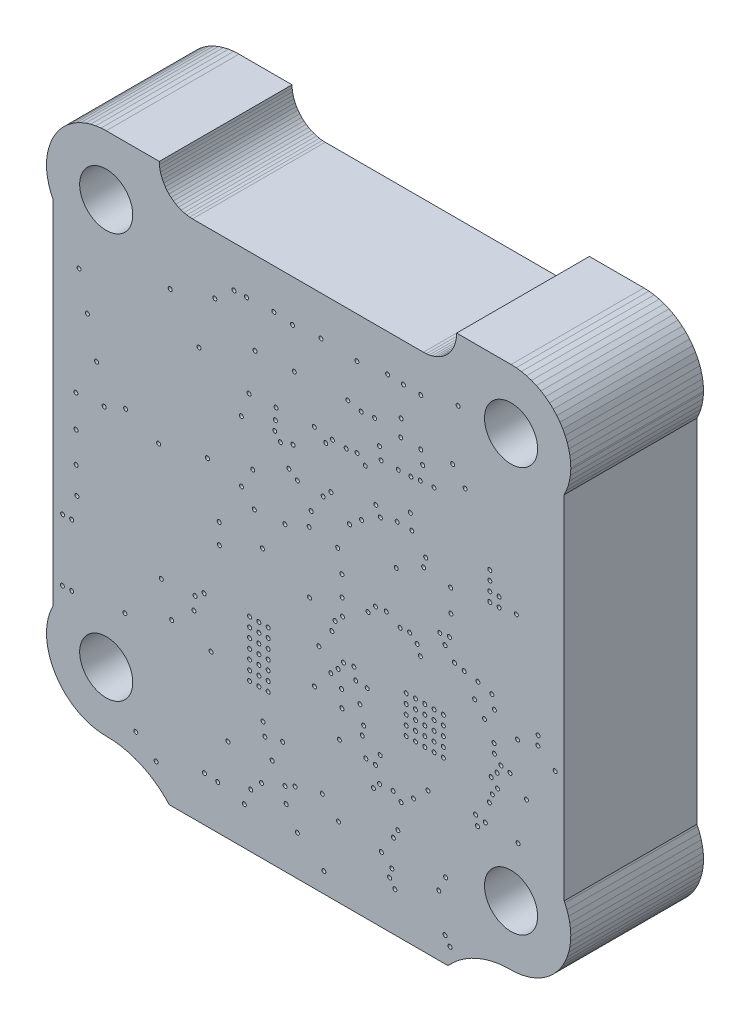
SolidWorks part; units mm, degrees
ref_plane "Спереди" through (0, 0, 0) normal (0, 0, 1) x (1, 0, 0)
ref_plane "Сверху" through (0, 0, 0) normal (0, 1, 0) x (1, 0, 0)
ref_plane "Справа" through (0, 0, 0) normal (1, 0, 0) x (0, 0, -1)
sketch "Model" plane through (0, 0, 0) normal (0, 0, 1) x (1, 0, 0)
  line L0 (0, 6.6) -> (0.0171, 6.2078)
  line L1 (0.0171, 6.2078) -> (0.0684, 5.8186)
  line L2 (0.0684, 5.8186) -> (0.1533, 5.4353)
  line L3 (0.1533, 5.4353) -> (0.2714, 5.0609)
  line L4 (0.2714, 5.0609) -> (0.4216, 4.6982)
  line L5 (0.4216, 4.6982) -> (0.6029, 4.35)
  line L6 (0.6029, 4.35) -> (0.8138, 4.0189)
  line L7 (0.8138, 4.0189) -> (1.0528, 3.7075)
  line L8 (1.0528, 3.7075) -> (1.318, 3.418)
  line L9 (1.318, 3.418) -> (1.6075, 3.1528)
  line L10 (1.6075, 3.1528) -> (1.9189, 2.9138)
  line L11 (1.9189, 2.9138) -> (2.25, 2.7029)
  line L12 (2.25, 2.7029) -> (2.5982, 2.5216)
  line L13 (2.5982, 2.5216) -> (2.9609, 2.3714)
  line L14 (2.9609, 2.3714) -> (3.3353, 2.2533)
  line L15 (3.3353, 2.2533) -> (3.7186, 2.1684)
  line L16 (3.7186, 2.1684) -> (4.1078, 2.1171)
  line L17 (4.1078, 2.1171) -> (4.5, 2.1)
  line L18 (4.5, 2.1) -> (5.0556, 2.0776)
  line L19 (5.0556, 2.0776) -> (5.6071, 2.0069)
  line L20 (5.6071, 2.0069) -> (6.1503, 1.8884)
  line L21 (6.1503, 1.8884) -> (6.6811, 1.723)
  line L22 (6.6811, 1.723) -> (7.1955, 1.5119)
  line L23 (7.1955, 1.5119) -> (7.6896, 1.2569)
  line L24 (7.6896, 1.2569) -> (8.1595, 0.9597)
  line L25 (8.1595, 0.9597) -> (8.6018, 0.6227)
  line L26 (8.6018, 0.6227) -> (9.013, 0.2484)
  line L27 (9.013, 0.2484) -> (9.25, 0)
  line L28 (9.25, 0) -> (30.25, 0)
  line L29 (30.25, 0) -> (30.6405, 0.3959)
  line L30 (30.6405, 0.3959) -> (31.0639, 0.7562)
  line L31 (31.0639, 0.7562) -> (31.5172, 1.0782)
  line L32 (31.5172, 1.0782) -> (31.9968, 1.3595)
  line L33 (31.9968, 1.3595) -> (32.4991, 1.598)
  line L34 (32.4991, 1.598) -> (33.0202, 1.7917)
  line L35 (33.0202, 1.7917) -> (33.5563, 1.9393)
  line L36 (33.5563, 1.9393) -> (34.1032, 2.0396)
  line L37 (34.1032, 2.0396) -> (34.6567, 2.0919)
  line L38 (34.6567, 2.0919) -> (35, 2.1)
  line L39 (35, 2.1) -> (35.3922, 2.1171)
  line L40 (35.3922, 2.1171) -> (35.7814, 2.1684)
  line L41 (35.7814, 2.1684) -> (36.1647, 2.2533)
  line L42 (36.1647, 2.2533) -> (36.5391, 2.3714)
  line L43 (36.5391, 2.3714) -> (36.9018, 2.5216)
  line L44 (36.9018, 2.5216) -> (37.25, 2.7029)
  line L45 (37.25, 2.7029) -> (37.5811, 2.9138)
  line L46 (37.5811, 2.9138) -> (37.8925, 3.1528)
  line L47 (37.8925, 3.1528) -> (38.182, 3.418)
  line L48 (38.182, 3.418) -> (38.4472, 3.7075)
  line L49 (38.4472, 3.7075) -> (38.6862, 4.0189)
  line L50 (38.6862, 4.0189) -> (38.8971, 4.35)
  line L51 (38.8971, 4.35) -> (39.0784, 4.6982)
  line L52 (39.0784, 4.6982) -> (39.2286, 5.0609)
  line L53 (39.2286, 5.0609) -> (39.3467, 5.4353)
  line L54 (39.3467, 5.4353) -> (39.4316, 5.8186)
  line L55 (39.4316, 5.8186) -> (39.4829, 6.2078)
  line L56 (39.4829, 6.2078) -> (39.5, 6.6)
  line L57 (39.5, 6.6) -> (39.4778, 6.9908)
  line L58 (39.4778, 6.9908) -> (39.4216, 7.3781)
  line L59 (39.4216, 7.3781) -> (39.3319, 7.7591)
  line L60 (39.3319, 7.7591) -> (39.2093, 8.1308)
  line L61 (39.2093, 8.1308) -> (39.0547, 8.4904)
  line L62 (39.0547, 8.4904) -> (39, 8.6)
  line L63 (39, 8.6) -> (39, 35.1)
  line L64 (39, 35.1) -> (39.1643, 35.4552)
  line L65 (39.1643, 35.4552) -> (39.297, 35.8235)
  line L66 (39.297, 35.8235) -> (39.3971, 36.2018)
  line L67 (39.3971, 36.2018) -> (39.4638, 36.5875)
  line L68 (39.4638, 36.5875) -> (39.4967, 36.9775)
  line L69 (39.4967, 36.9775) -> (39.5, 37.1)
  line L70 (39.5, 37.1) -> (39.4829, 37.4922)
  line L71 (39.4829, 37.4922) -> (39.4316, 37.8814)
  line L72 (39.4316, 37.8814) -> (39.3467, 38.2647)
  line L73 (39.3467, 38.2647) -> (39.2286, 38.6391)
  line L74 (39.2286, 38.6391) -> (39.0784, 39.0018)
  line L75 (39.0784, 39.0018) -> (38.8971, 39.35)
  line L76 (38.8971, 39.35) -> (38.6862, 39.6811)
  line L77 (38.6862, 39.6811) -> (38.4472, 39.9925)
  line L78 (38.4472, 39.9925) -> (38.182, 40.282)
  line L79 (38.182, 40.282) -> (37.8925, 40.5472)
  line L80 (37.8925, 40.5472) -> (37.5811, 40.7862)
  line L81 (37.5811, 40.7862) -> (37.25, 40.9971)
  line L82 (37.25, 40.9971) -> (36.9018, 41.1784)
  line L83 (36.9018, 41.1784) -> (36.5391, 41.3286)
  line L84 (36.5391, 41.3286) -> (36.1647, 41.4467)
  line L85 (36.1647, 41.4467) -> (35.7814, 41.5316)
  line L86 (35.7814, 41.5316) -> (35.3922, 41.5829)
  line L87 (35.3922, 41.5829) -> (35, 41.6)
  line L88 (35, 41.6) -> (30.9, 41.6)
  line L89 (30.9, 41.6) -> (30.8905, 41.3821)
  line L90 (30.8905, 41.3821) -> (30.862, 41.1659)
  line L91 (30.862, 41.1659) -> (30.8148, 40.953)
  line L92 (30.8148, 40.953) -> (30.7492, 40.745)
  line L93 (30.7492, 40.745) -> (30.6658, 40.5435)
  line L94 (30.6658, 40.5435) -> (30.5651, 40.35)
  line L95 (30.5651, 40.35) -> (30.4479, 40.1661)
  line L96 (30.4479, 40.1661) -> (30.3151, 39.993)
  line L97 (30.3151, 39.993) -> (30.1678, 39.8322)
  line L98 (30.1678, 39.8322) -> (30.007, 39.6849)
  line L99 (30.007, 39.6849) -> (29.8339, 39.5521)
  line L100 (29.8339, 39.5521) -> (29.65, 39.4349)
  line L101 (29.65, 39.4349) -> (29.4565, 39.3342)
  line L102 (29.4565, 39.3342) -> (29.2551, 39.2508)
  line L103 (29.2551, 39.2508) -> (29.047, 39.1852)
  line L104 (29.047, 39.1852) -> (28.8341, 39.138)
  line L105 (28.8341, 39.138) -> (28.6179, 39.1095)
  line L106 (28.6179, 39.1095) -> (28.4, 39.1)
  line L107 (28.4, 39.1) -> (11, 39.1)
  line L108 (11, 39.1) -> (10.7821, 39.1095)
  line L109 (10.7821, 39.1095) -> (10.5659, 39.138)
  line L110 (10.5659, 39.138) -> (10.353, 39.1852)
  line L111 (10.353, 39.1852) -> (10.1449, 39.2508)
  line L112 (10.1449, 39.2508) -> (9.9435, 39.3342)
  line L113 (9.9435, 39.3342) -> (9.75, 39.4349)
  line L114 (9.75, 39.4349) -> (9.5661, 39.5521)
  line L115 (9.5661, 39.5521) -> (9.393, 39.6849)
  line L116 (9.393, 39.6849) -> (9.2322, 39.8322)
  line L117 (9.2322, 39.8322) -> (9.0849, 39.993)
  line L118 (9.0849, 39.993) -> (8.9521, 40.1661)
  line L119 (8.9521, 40.1661) -> (8.8349, 40.35)
  line L120 (8.8349, 40.35) -> (8.7342, 40.5435)
  line L121 (8.7342, 40.5435) -> (8.6508, 40.745)
  line L122 (8.6508, 40.745) -> (8.5852, 40.953)
  line L123 (8.5852, 40.953) -> (8.538, 41.1659)
  line L124 (8.538, 41.1659) -> (8.5095, 41.3821)
  line L125 (8.5095, 41.3821) -> (8.5, 41.6)
  line L126 (8.5, 41.6) -> (4.5, 41.6)
  line L127 (4.5, 41.6) -> (4.1078, 41.5829)
  line L128 (4.1078, 41.5829) -> (3.7186, 41.5316)
  line L129 (3.7186, 41.5316) -> (3.3353, 41.4467)
  line L130 (3.3353, 41.4467) -> (2.9609, 41.3286)
  line L131 (2.9609, 41.3286) -> (2.5982, 41.1784)
  line L132 (2.5982, 41.1784) -> (2.25, 40.9971)
  line L133 (2.25, 40.9971) -> (1.9189, 40.7862)
  line L134 (1.9189, 40.7862) -> (1.6075, 40.5472)
  line L135 (1.6075, 40.5472) -> (1.318, 40.282)
  line L136 (1.318, 40.282) -> (1.0528, 39.9925)
  line L137 (1.0528, 39.9925) -> (0.8138, 39.6811)
  line L138 (0.8138, 39.6811) -> (0.6029, 39.35)
  line L139 (0.6029, 39.35) -> (0.4216, 39.0018)
  line L140 (0.4216, 39.0018) -> (0.2714, 38.6391)
  line L141 (0.2714, 38.6391) -> (0.1533, 38.2647)
  line L142 (0.1533, 38.2647) -> (0.0684, 37.8814)
  line L143 (0.0684, 37.8814) -> (0.0171, 37.4922)
  line L144 (0.0171, 37.4922) -> (0, 37.1)
  line L145 (0, 37.1) -> (0.0222, 36.7092)
  line L146 (0.0222, 36.7092) -> (0.0784, 36.3219)
  line L147 (0.0784, 36.3219) -> (0.1681, 35.9409)
  line L148 (0.1681, 35.9409) -> (0.2907, 35.5692)
  line L149 (0.2907, 35.5692) -> (0.4453, 35.2096)
  line L150 (0.4453, 35.2096) -> (0.5, 35.1)
  line L151 (0.5, 35.1) -> (0.5, 8.6)
  line L152 (0.5, 8.6) -> (0.3357, 8.2448)
  line L153 (0.3357, 8.2448) -> (0.203, 7.8765)
  line L154 (0.203, 7.8765) -> (0.1029, 7.4982)
  line L155 (0.1029, 7.4982) -> (0.0362, 7.1125)
  line L156 (0.0362, 7.1125) -> (0.0033, 6.7225)
  line L157 (0.0033, 6.7225) -> (0, 6.6)
  circle A0 centre (4.5, 37.1) radius 2
  circle A1 centre (35, 37.1) radius 2
  circle A2 centre (4.5, 6.6) radius 2
  circle A3 centre (35, 6.6) radius 2
  circle A4 centre (4.343, 23.53) radius 0.15
  circle A5 centre (14.68, 28.07) radius 0.15
  circle A6 centre (3.08, 28.96) radius 0.15
  circle A7 centre (2.45, 31.59) radius 0.15
  circle A8 centre (17.96, 22.66) radius 0.15
  circle A9 centre (16.27, 20.24) radius 0.15
  circle A10 centre (14.69, 23.49) radius 0.15
  circle A11 centre (18.9, 25.99) radius 0.15
  circle A12 centre (17.6227, 27.8373) radius 0.15
  circle A13 centre (16, 13.2) radius 0.15
  circle A14 centre (28.5, 14.8) radius 0.15
  circle A15 centre (22.26, 12.8) radius 0.15
  circle A16 centre (8.45, 23.16) radius 0.15
  circle A17 centre (12.13, 24.05) radius 0.15
  circle A18 centre (36.16, 13.79) radius 0.15
  circle A19 centre (20.9, 1.5) radius 0.15
  circle A20 centre (16.45, 8.04) radius 0.15
  circle A21 centre (25.14, 11.18) radius 0.15
  circle A22 centre (21.0406, 29.502) radius 0.15
  circle A23 centre (30.0657, 5.6743) radius 0.15
  circle A24 centre (31.01, 36.91) radius 0.15
  circle A25 centre (29.19, 30.67) radius 0.15
  circle A26 centre (23.39, 36.01) radius 0.15
  circle A27 centre (18.53, 35.952) radius 0.15
  circle A28 centre (22.7, 33.11) radius 0.15
  circle A29 centre (15.07, 36.02) radius 0.15
  circle A30 centre (38.325, 16.73) radius 0.15
  circle A31 centre (35.49, 17.368) radius 0.15
  circle A32 centre (37.02, 17.743) radius 0.15
  circle A33 centre (19.79, 23.4) radius 0.15
  circle A34 centre (22.83, 25.09) radius 0.15
  circle A35 centre (26.69, 32.69) radius 0.15
  circle A36 centre (35.53, 10.63) radius 0.15
  circle A37 centre (30.4, 1.31) radius 0.15
  circle A38 centre (22, 5.28) radius 0.15
  circle A39 centre (25.23, 4.908) radius 0.15
  circle A40 centre (1.9, 14.93) radius 0.15
  circle A41 centre (1.22, 14.93) radius 0.15
  circle A42 centre (1.9, 10.28) radius 0.15
  circle A43 centre (1.2, 10.27) radius 0.15
  circle A44 centre (25.21, 30.45) radius 0.15
  circle A45 centre (22.58, 29.91) radius 0.15
  circle A46 centre (35.4, 25.5) radius 0.15
  circle A47 centre (28.57, 25.79) radius 0.15
  circle A48 centre (26.42, 27.05) radius 0.15
  circle A49 centre (33.4, 27.4) radius 0.15
  circle A50 centre (33.4, 26.7) radius 0.15
  circle A51 centre (33.4, 26) radius 0.15
  circle A52 centre (33.4, 25.3) radius 0.15
  circle A53 centre (34.1, 25.3) radius 0.15
  circle A54 centre (34.1, 26) radius 0.15
  circle A55 centre (29.2, 14.8) radius 0.15
  circle A56 centre (29.2, 14.1) radius 0.15
  circle A57 centre (28.5, 14.1) radius 0.15
  circle A58 centre (27.8, 14.1) radius 0.15
  circle A59 centre (27.8, 14.8) radius 0.15
  circle A60 centre (27.8, 15.5) radius 0.15
  circle A61 centre (28.5, 15.5) radius 0.15
  circle A62 centre (29.2, 15.5) radius 0.15
  circle A63 centre (28.5, 16.2) radius 0.15
  circle A64 centre (27.8, 16.2) radius 0.15
  circle A65 centre (27.1, 16.2) radius 0.15
  circle A66 centre (27.1, 15.5) radius 0.15
  circle A67 centre (27.1, 14.8) radius 0.15
  circle A68 centre (27.1, 14.1) radius 0.15
  circle A69 centre (27.1, 13.4) radius 0.15
  circle A70 centre (27.8, 13.4) radius 0.15
  circle A71 centre (28.5, 13.4) radius 0.15
  circle A72 centre (29.2, 13.4) radius 0.15
  circle A73 centre (29.2, 16.2) radius 0.15
  circle A74 centre (29.9, 16.2) radius 0.15
  circle A75 centre (29.9, 15.5) radius 0.15
  circle A76 centre (29.9, 14.8) radius 0.15
  circle A77 centre (29.9, 14.1) radius 0.15
  circle A78 centre (29.9, 13.4) radius 0.15
  circle A79 centre (16, 13.9) radius 0.15
  circle A80 centre (16, 14.6) radius 0.15
  circle A81 centre (16, 15.3) radius 0.15
  circle A82 centre (16, 12.5) radius 0.15
  circle A83 centre (16, 11.8) radius 0.15
  circle A84 centre (16, 11.1) radius 0.15
  circle A85 centre (15.3, 11.1) radius 0.15
  circle A86 centre (15.3, 11.8) radius 0.15
  circle A87 centre (15.3, 12.5) radius 0.15
  circle A88 centre (15.3, 13.2) radius 0.15
  circle A89 centre (15.3, 13.9) radius 0.15
  circle A90 centre (15.3, 14.6) radius 0.15
  circle A91 centre (15.3, 15.3) radius 0.15
  circle A92 centre (16.7, 15.3) radius 0.15
  circle A93 centre (16.7, 14.6) radius 0.15
  circle A94 centre (16.7, 13.9) radius 0.15
  circle A95 centre (16.7, 13.2) radius 0.15
  circle A96 centre (16.7, 12.5) radius 0.15
  circle A97 centre (16.7, 11.8) radius 0.15
  circle A98 centre (16.7, 11.1) radius 0.15
  circle A99 centre (24.63, 8.78) radius 0.15
  circle A100 centre (21.54, 29.96) radius 0.15
  circle A101 centre (24.78, 10.37) radius 0.15
  circle A102 centre (21.43, 26.49) radius 0.15
  circle A103 centre (33.748, 15.576) radius 0.15
  circle A104 centre (18.57, 28.15) radius 0.15
  circle A105 centre (34.2371, 15.0577) radius 0.15
  circle A106 centre (17.198, 28.37) radius 0.15
  circle A107 centre (33.5, 13.93) radius 0.15
  circle A108 centre (17.3, 29.93) radius 0.15
  circle A109 centre (33.948, 14.4394) radius 0.15
  circle A110 centre (17.25, 29.09) radius 0.15
  circle A111 centre (2.29, 16.67) radius 0.15
  circle A112 centre (2.23, 18.67) radius 0.15
  circle A113 centre (2.23, 20.96) radius 0.15
  circle A114 centre (2.21, 23.37) radius 0.15
  circle A115 centre (18.67, 32.97) radius 0.15
  circle A116 centre (24.72, 32.97) radius 0.15
  circle A117 centre (31.5398, 31.7798) radius 0.15
  circle A118 centre (27.52, 27.02) radius 0.15
  circle A119 centre (30.47, 23.08) radius 0.15
  circle A120 centre (9.32, 33.68) radius 0.15
  circle A121 centre (5.96, 24.19) radius 0.15
  circle A122 centre (26.25, 2.99) radius 0.15
  circle A123 centre (18.9, 3) radius 0.15
  circle A124 centre (26.64, 20.24) radius 0.15
  circle A125 centre (18.73, 5.93) radius 0.15
  circle A126 centre (27.36, 20.29) radius 0.15
  circle A127 centre (20.778, 6.48) radius 0.15
  circle A128 centre (26.468, 6.95) radius 0.15
  circle A129 centre (32.47, 10.21) radius 0.15
  circle A130 centre (17.97, 5.59) radius 0.15
  circle A131 centre (16.2, 4.9) radius 0.15
  circle A132 centre (34.9141, 14.91) radius 0.15
  circle A133 centre (26.35, 24) radius 0.15
  circle A134 centre (37.04, 18.42) radius 0.15
  circle A135 centre (24.0164, 29.502) radius 0.15
  circle A136 centre (23.74, 25.825) radius 0.15
  circle A137 centre (23.3, 15.13) radius 0.15
  circle A138 centre (22.07, 10.65) radius 0.15
  circle A139 centre (13.01, 20.33) radius 0.15
  circle A140 centre (15.2607, 29.8293) radius 0.15
  circle A141 centre (11.49, 30.96) radius 0.15
  circle A142 centre (17, 6.76) radius 0.15
  circle A143 centre (28.17, 19.15) radius 0.15
  circle A144 centre (27.4105, 28.1296) radius 0.15
  circle A145 centre (27.92, 19.83) radius 0.15
  circle A146 centre (25.15, 26.7) radius 0.15
  circle A147 centre (26.89, 36.24) radius 0.15
  circle A148 centre (26.503, 30.48) radius 0.15
  circle A149 centre (28.16, 30.6) radius 0.15
  circle A150 centre (28.198, 36.21) radius 0.15
  circle A151 centre (23.71, 32.88) radius 0.15
  circle A152 centre (26.72, 33.95) radius 0.15
  circle A153 centre (26.11, 9.34) radius 0.15
  circle A154 centre (23.4, 30.023) radius 0.15
  circle A155 centre (26.71, 8.9) radius 0.15
  circle A156 centre (20.18, 30.123) radius 0.15
  circle A157 centre (33.06, 10.75) radius 0.15
  circle A158 centre (30.4475, 24.772) radius 0.15
  circle A159 centre (26.02, 4.2247) radius 0.15
  circle A160 centre (32.325, 10.895) radius 0.15
  circle A161 centre (28.412, 25.072) radius 0.15
  circle A162 centre (25.8503, 3.5477) radius 0.15
  circle A163 centre (33.9737, 13.4237) radius 0.15
  circle A164 centre (28.198, 32.66) radius 0.15
  circle A165 centre (23.9, 12.487) radius 0.15
  circle A166 centre (20.52, 15.978) radius 0.15
  circle A167 centre (23.61, 13.74) radius 0.15
  circle A168 centre (21.5, 17.46) radius 0.15
  circle A169 centre (20.1895, 13.192) radius 0.15
  circle A170 centre (23.79, 11.79) radius 0.15
  circle A171 centre (22.23, 14.05) radius 0.15
  circle A172 centre (20.68, 36.14) radius 0.15
  circle A173 centre (25.7, 36.3) radius 0.15
  circle A174 centre (30.6, 32.9) radius 0.15
  circle A175 centre (28.34, 31.71) radius 0.15
  circle A176 centre (12.68, 34.75) radius 0.15
  circle A177 centre (6.73, 3.5) radius 0.15
  circle A178 centre (15.54, 25.01) radius 0.15
  circle A179 centre (27.45, 30.51) radius 0.15
  circle A180 centre (25.087, 31.3133) radius 0.15
  circle A181 centre (16.31, 8.96) radius 0.15
  circle A182 centre (12.4, 11.57) radius 0.15
  circle A183 centre (11.87, 15.11) radius 0.15
  circle A184 centre (13.03, 18.82) radius 0.15
  circle A185 centre (11.108, 13.6005) radius 0.15
  circle A186 centre (31.467, 19.8338) radius 0.15
  circle A187 centre (21.74, 18.24) radius 0.15
  circle A188 centre (30.357, 21.5011) radius 0.15
  circle A189 centre (19.82, 18.8) radius 0.15
  circle A190 centre (30.74, 20.01) radius 0.15
  circle A191 centre (22.3, 18.81) radius 0.15
  circle A192 centre (29.63, 21.41) radius 0.15
  circle A193 centre (22.26, 21.55) radius 0.15
  circle A194 centre (27.65, 9.61) radius 0.15
  circle A195 centre (30.03, 1.88) radius 0.15
  circle A196 centre (28.74, 10.67) radius 0.15
  circle A197 centre (29.555, 4.555) radius 0.15
  circle A198 centre (26.135, 6.288) radius 0.15
  circle A199 centre (33.59, 12.85) radius 0.15
  circle A200 centre (33.55, 19.37) radius 0.15
  circle A201 centre (15.39, 4.07) radius 0.15
  circle A202 centre (5.91, 10.83) radius 0.15
  circle A203 centre (33.36, 12.21) radius 0.15
  circle A204 centre (33.74, 18.45) radius 0.15
  circle A205 centre (24.06, 10.433) radius 0.15
  circle A206 centre (23.157, 15.963) radius 0.15
  circle A207 centre (33, 17.47) radius 0.15
  circle A208 centre (24.79, 20.7) radius 0.15
  circle A209 centre (21.97, 15.22) radius 0.15
  circle A210 centre (18.26, 26.43) radius 0.15
  circle A211 centre (14.91, 2.86) radius 0.15
  circle A212 centre (13.67, 6.34) radius 0.15
  circle A213 centre (21.94, 23.11) radius 0.15
  circle A214 centre (32.25, 18.38) radius 0.15
  circle A215 centre (24.81, 27.35) radius 0.15
  circle A216 centre (15.71, 32.85) radius 0.15
  circle A217 centre (17.13, 36.1) radius 0.15
  circle A218 centre (8.65, 14.44) radius 0.15
  circle A219 centre (14.123, 36) radius 0.15
  circle A220 centre (25.0937, 9.2837) radius 0.15
  circle A221 centre (15.66, 22.47) radius 0.15
  circle A222 centre (33.72, 16.253) radius 0.15
  circle A223 centre (18.06, 4.45) radius 0.15
  circle A224 centre (32.5, 19.65) radius 0.15
  circle A225 centre (3.77, 26.17) radius 0.15
  circle A226 centre (30.03, 20.8) radius 0.15
  circle A227 centre (22.27, 20.04) radius 0.15
  circle A228 centre (25.6, 20.78) radius 0.15
  circle A229 centre (22.37, 15.84) radius 0.15
  circle A230 centre (20.84, 25.91) radius 0.15
  circle A231 centre (24.23, 20.06) radius 0.15
  circle A232 centre (21.42, 14.67) radius 0.15
  circle A233 centre (19.94, 24.51) radius 0.15
  circle A234 centre (8.26, 2.33) radius 0.15
  circle A235 centre (12.9, 3.31) radius 0.15
  circle A236 centre (9.43, 12.14) radius 0.15
  circle A237 centre (11.19, 14.6) radius 0.15
  circle A238 centre (24.16, 15.06) radius 0.15
  circle A239 centre (17.79, 8.38) radius 0.15
  circle A240 centre (11.9, 3.39) radius 0.15
extrude "Бобышка-Вытянуть1" add sketch "Model" along normal blind 10 contours L156 L157 L0 L1 L2 L3 L4 L5 L6 L7 L8 L9 L10 L11 L12 L13 L14 L15 L16 L17 L18 L19 L20 L21 L22 L23 L24 L25 L26 L27 L28 L29 L30 L31 L32 L33 L34 L35 L36 L37 L38 L39 L40 L41 L42 L43 L44 L45 L46 L47 L48
sketch "Эскиз2" plane through (0, 0, 10) normal (0, 0, 1) x (1, 0, 0)
  line L0 (9.25, 0) -> (30.25, 0) construction
  line L1 (0.0171, 41.6) -> (39.4829, 41.6)
  line L2 (0.0171, 41.6) -> (0.0171, 0)
  line L3 (0.0171, 0) -> (39.4829, 0)
  line L4 (39.4829, 41.6) -> (39.4829, 0)
  line L5 (0.0171, 41.6) -> (39.4829, 0) construction
  line L6 (0.0171, 0) -> (39.4829, 41.6) construction
  line L7 (8.5, 41.6) -> (4.5, 41.6) construction
  point P0 (19.75, 20.8)
